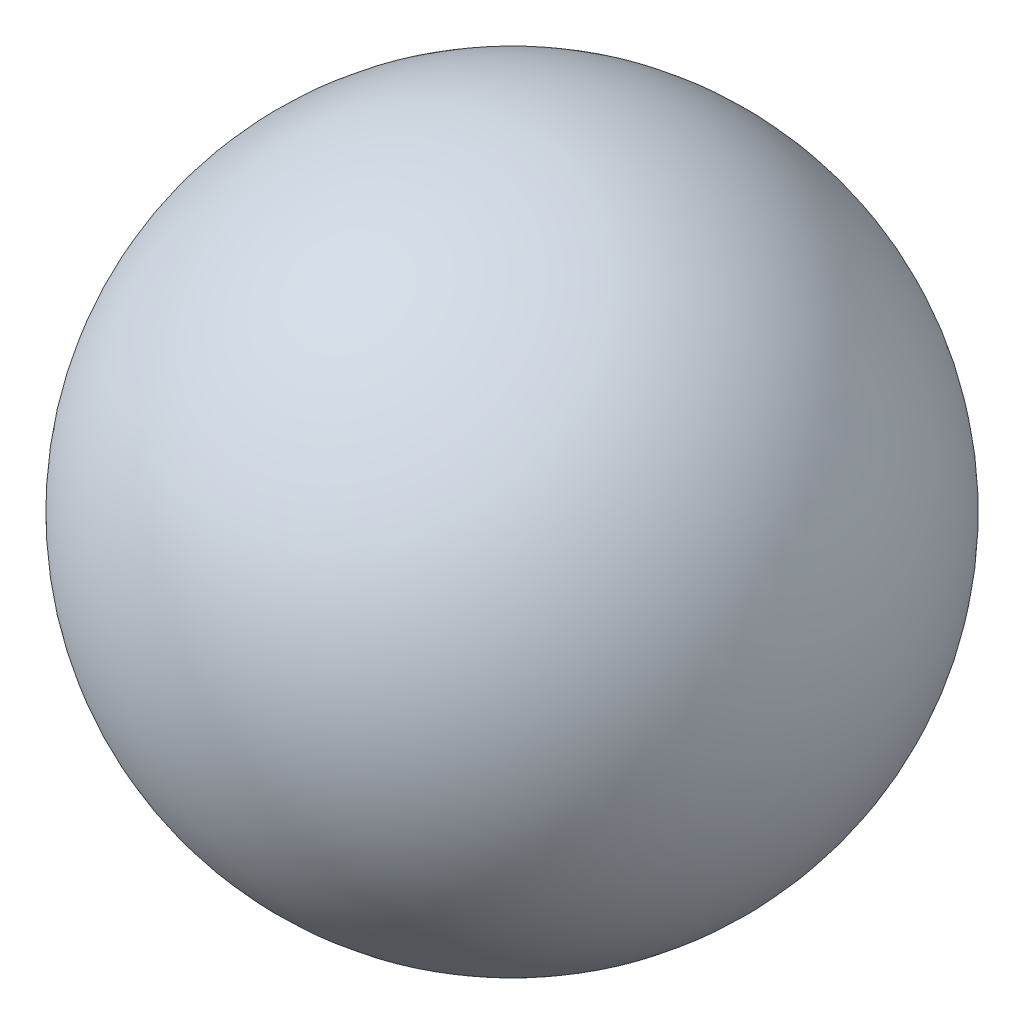
SolidWorks part; units mm, degrees
ref_plane "Front" through (0, 0, 0) normal (0, 0, 1) x (1, 0, 0)
ref_plane "Top" through (0, 0, 0) normal (0, 1, 0) x (1, 0, 0)
ref_plane "Right" through (0, 0, 0) normal (1, 0, 0) x (0, 0, -1)
sketch "Sketch2" plane through (0, 0, 0) normal (0, 0, 1) x (1, 0, 0)
  line L0 (0, 88.9) -> (0, -88.9)
  arc A0 (0, 88.9) -> (0, -88.9) centre (0, 0) ccw
  point P5 (0, 0)
  dimension "D1" = 177.8
revolve "Revolve3" add sketch "Sketch2" angle 360 about L0
